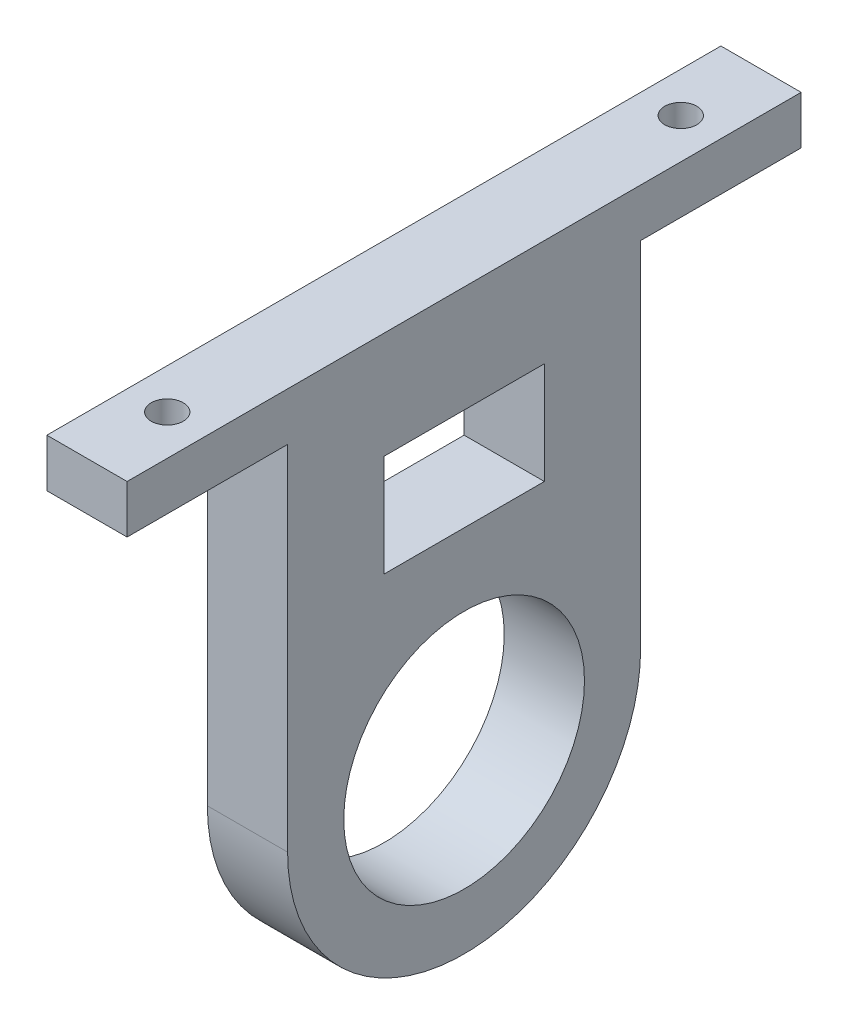
SolidWorks part; units mm, degrees
ref_plane "Front Plane" through (0, 0, 0) normal (0, 0, 1) x (1, 0, 0)
ref_plane "Top Plane" through (0, 0, 0) normal (0, 1, 0) x (1, 0, 0)
ref_plane "Right Plane" through (0, 0, 0) normal (1, 0, 0) x (0, 0, -1)
sketch "Sketch1" plane through (0, 0, 0) normal (1, 0, 0) x (0, 0, -1)
  circle A0 centre (0, 0) radius 7.5
extrude "Extrude-Thin1" add sketch "Sketch1" along normal blind 5 thin contours A0
sketch "Sketch2" plane through (0, 0, 0) normal (1, 0, 0) x (0, 0, -1)
  line L1 (-11, 0) -> (-11, 25)
  line L2 (11, 0) -> (11, 25)
  line L3 (-11, 25) -> (11, 25)
  circle A0 centre (0, 0) radius 11 construction
  arc A1 (-11, 0) -> (11, 0) centre (0, 0) cw
extrude "Boss-Extrude2" add sketch "Sketch2" along normal blind 5 contours L1 A1 L2 L3
sketch "Sketch4" plane through (0, 0, -11) normal (0, 0, -1) x (-1, 0, 0)
  line L0 (-5, 0) -> (-5, 25) construction
  line L1 (0, 25) -> (-5, 25)
  line L2 (0, 25) -> (0, 22)
  line L3 (0, 22) -> (-5, 22)
  line L4 (-5, 25) -> (-5, 22)
extrude "Boss-Extrude3" add sketch "Sketch4" along normal blind 10
sketch "Sketch5" plane through (0, 25, 0) normal (0, 1, 0) x (1, 0, 0)
  circle A0 centre (2.5, 16) radius 1
extrude "Cut-Extrude1" cut sketch "Sketch5" against normal blind 5
pattern_linear "LPattern1" count 2 spacing 32 along (0, 0, 1) of "Cut-Extrude1", "Boss-Extrude3"
sketch "Sketch6" plane through (5, 0, 0) normal (1, 0, 0) x (0, 0, -1)
  line L2 (-5, 12) -> (5, 12)
  line L3 (-5, 12) -> (-5, 18.354)
  line L4 (-5, 18.354) -> (5, 18.354)
  line L5 (5, 12) -> (5, 18.354)
  line L6 (-5, 12) -> (5, 18.354) construction
  line L7 (-5, 18.354) -> (5, 12) construction
extrude "Cut-Extrude2" cut sketch "Sketch6" against normal blind 5 contours L3 L2 L5 L4
